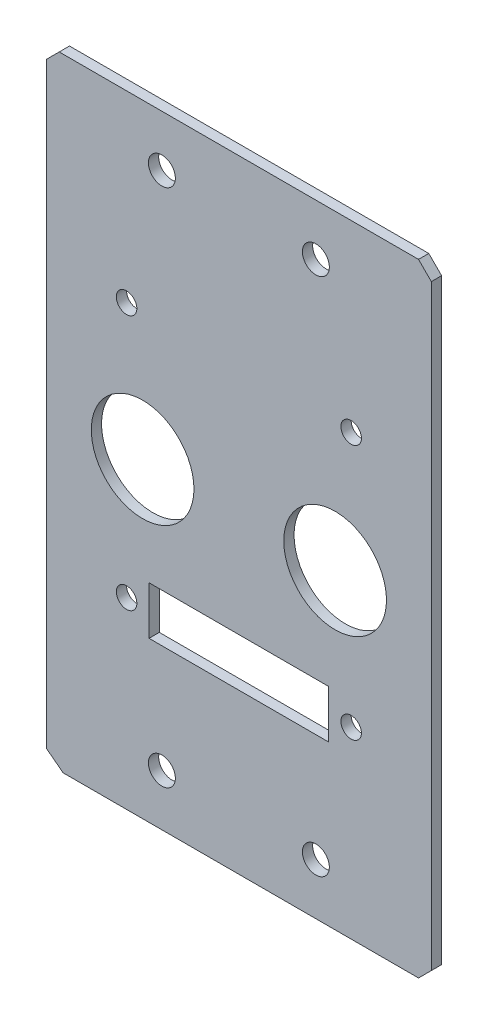
SolidWorks part; units mm, degrees
ref_plane "前视基准面" through (0, 0, 0) normal (0, 0, 1) x (1, 0, 0)
ref_plane "上视基准面" through (0, 0, 0) normal (0, 1, 0) x (1, 0, 0)
ref_plane "右视基准面" through (0, 0, 0) normal (1, 0, 0) x (0, 0, -1)
sketch "草图1" plane through (0, 0, 0) normal (0, 0, 1) x (1, 0, 0)
  line L0 (-92.1038, 0) -> (123.6031, 0) construction
  line L1 (-28, 48.5) -> (28, 48.5)
  line L2 (-30, 46.5) -> (-30, -46.5)
  line L3 (-27.3896, -48.5) -> (28, -48.5)
  line L4 (30, 46.5) -> (30, -46.5)
  line L5 (0, 53.0447) -> (0, -100.1676) construction
  line L6 (-35.7434, -19.9) -> (41.482, -19.9) construction
  line L7 (-30, 46.5) -> (-28, 48.5)
  line L8 (-14, -16.15) -> (14, -16.15)
  line L9 (-14, -16.15) -> (-14, -23.65)
  line L10 (-14, -23.65) -> (14, -23.65)
  line L11 (14, -16.15) -> (14, -23.65)
  line L12 (28, 48.5) -> (30, 46.5)
  line L13 (28, -48.5) -> (30, -46.5)
  line L14 (-30, -46.5) -> (-27.3896, -48.5)
  circle A0 centre (-15, 0) radius 8
  circle A1 centre (-17.5, 19.9) radius 1.6
  circle A2 centre (-12, 40.5) radius 2.1
  circle A3 centre (-17.5, -19.9) radius 1.6
  circle A4 centre (-12, -40.5) radius 2.1
  circle A5 centre (17.5, 19.9) radius 1.6
  circle A6 centre (12, 40.5) radius 2.1
  circle A7 centre (12, -40.5) radius 2.1
  circle A8 centre (17.5, -19.9) radius 1.6
  circle A9 centre (15, 0) radius 8
  dimension "D4" = 16
  dimension "D5" = 3.2
  dimension "D6" = 4.2
  dimension "D2" = 12
  dimension "D3" = 30
  dimension "D7" = 28.6
  dimension "D8" = 8
  dimension "D9" = 28
  dimension "D10" = 7.5
extrude "凸台-拉伸1" add sketch "草图1" along normal blind 1.6
